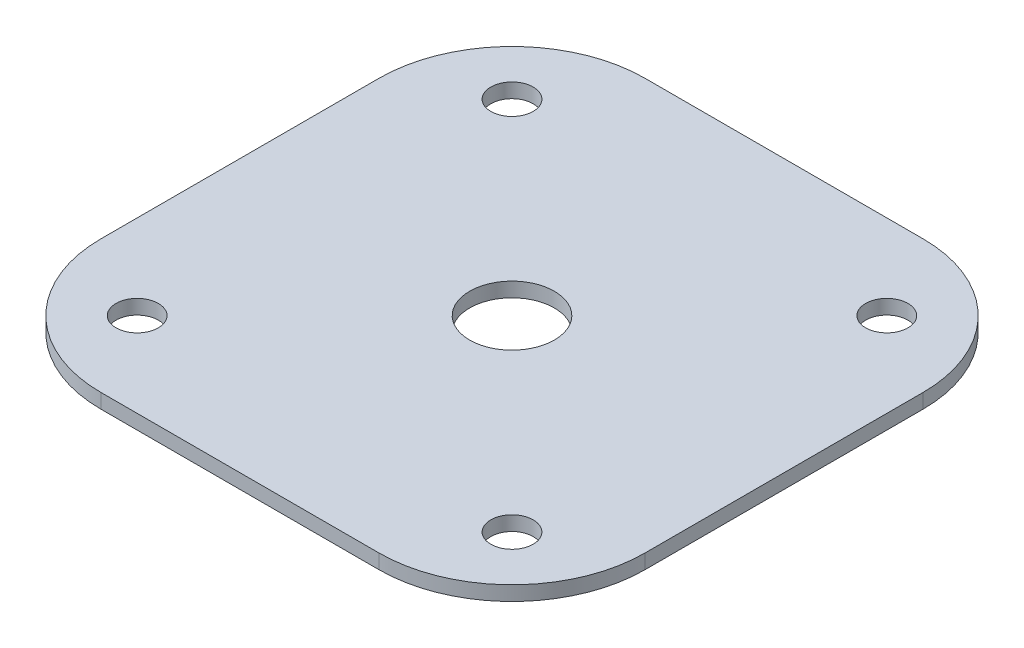
SolidWorks part; units mm, degrees
ref_plane "Front Plane" through (0, 0, 0) normal (0, 0, 1) x (1, 0, 0)
ref_plane "Top Plane" through (0, 0, 0) normal (0, 1, 0) x (1, 0, 0)
ref_plane "Right Plane" through (0, 0, 0) normal (1, 0, 0) x (0, 0, -1)
sketch "Sketch1" plane through (0, 0, 0) normal (0, 1, 0) x (1, 0, 0)
  line L0 (0, 0) -> (0, 22.5) construction
  line L1 (-11.5, 22.5) -> (11.5, 22.5)
  line L2 (-22.5, 11.5) -> (-22.5, -11.5)
  line L3 (-11.5, -22.5) -> (11.5, -22.5)
  line L4 (22.5, 11.5) -> (22.5, -11.5)
  line L5 (0, 0) -> (-22.5, 0) construction
  line L6 (0, 0) -> (-11.5, 11.5) construction
  line L7 (0, 0) -> (11.5, 11.5) construction
  circle A0 centre (0, 0) radius 3.5
  arc A1 (-22.5, -11.5) -> (-11.5, -22.5) centre (-11.5, -11.5) ccw
  arc A2 (11.5, -22.5) -> (22.5, -11.5) centre (11.5, -11.5) ccw
  arc A3 (11.5, 22.5) -> (22.5, 11.5) centre (11.5, 11.5) cw
  arc A4 (-11.5, 22.5) -> (-22.5, 11.5) centre (-11.5, 11.5) ccw
  circle A5 centre (0, 0) radius 21.9203 construction
  circle A6 centre (-15.5, 15.5) radius 1.75
  circle A7 centre (15.5, 15.5) radius 1.75
  circle A8 centre (15.5, -15.5) radius 1.75
  circle A9 centre (-15.5, -15.5) radius 1.75
  dimension "D1" = 7
  dimension "D4" = 11
  dimension "D5" = 3.5
  dimension "D6" = 31
  dimension "D2" = 45
  dimension "D3" = 45
extrude "Boss-Extrude1" add sketch "Sketch1" along normal blind 1.2
sketch "Sketch2" plane through (0, 0, 0) normal (0, 1, 0) x (1, 0, 0)
  line L0 (-22.5, 11.5) -> (-22.5, -11.5) construction
  line L3 (-12.1262, 5) -> (-28.5, 5)
  line L4 (-12.1262, 5) -> (-12.1262, -5)
  line L5 (-12.1262, -5) -> (-28.5, -5)
  line L6 (-30.5, 3) -> (-30.5, -3)
  arc A3 (-28.5, -5) -> (-30.5, -3) centre (-28.5, -3) cw
  arc A4 (-28.5, 5) -> (-30.5, 3) centre (-28.5, 3) ccw
  point P5 (-12.1262, 0)
  dimension "D2" = 2
  dimension "D1" = 10
  dimension "D3" = 8
extrude "Boss-Extrude2" [suppressed] add sketch "Sketch2" along normal up to surface (1.2 mm away)
fillet "Fillet1" [suppressed] radius 2
